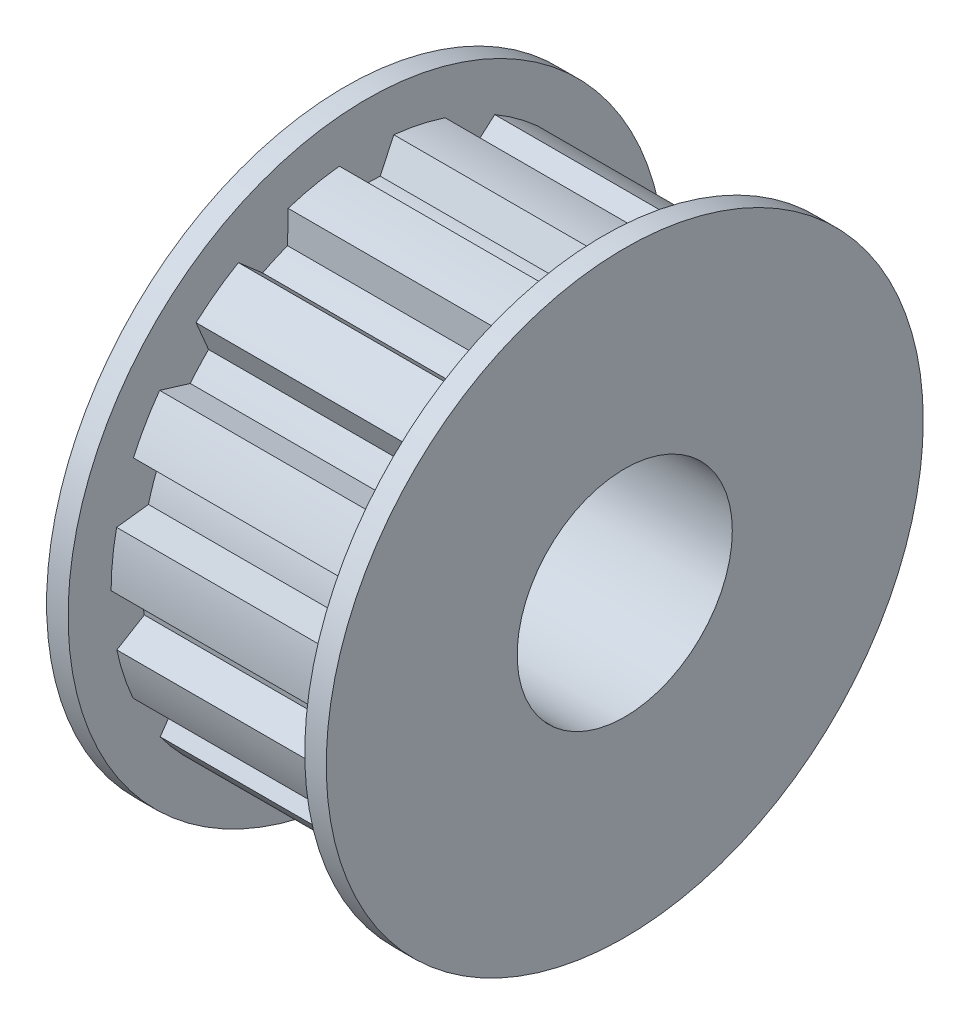
SolidWorks part; units mm, degrees
ref_plane "Front Plane" through (0, 0, 0) normal (0, 0, 1) x (1, 0, 0)
ref_plane "Top Plane" through (0, 0, 0) normal (0, 1, 0) x (1, 0, 0)
ref_plane "Right Plane" through (0, 0, 0) normal (1, 0, 0) x (0, 0, -1)
sketch "Sketch1" plane through (0, 0, 0) normal (1, 0, 0) x (0, 0, -1)
  line L0 (0, 11.875) -> (0, 0) construction
  circle A0 centre (0, 0) radius 11.875
  circle A1 centre (0, 0) radius 5
  point P19 (0, 0)
  dimension "D1" = 23.75
  dimension "D2" = 10
extrude "Boss-Extrude1" add sketch "Sketch1" along normal blind 11
sketch "Sketch2" plane through (0, 0, 0) normal (-1, 0, 0) x (0, 0, 1)
  line L0 (0, 0) -> (0, 11.875) construction
  line L1 (1.2649, 11.8074) -> (0.6346, 10.4558)
  line L2 (-1.2649, 11.8074) -> (-0.6346, 10.4558)
  line L3 (5.9581, 10.2721) -> (4.8325, 9.2937)
  line L4 (3.647, 11.3011) -> (3.673, 9.8099)
  line L5 (9.621, 6.9607) -> (8.1948, 6.5247)
  line L6 (7.9282, 8.8407) -> (7.3455, 7.4679)
  line L7 (11.6204, 2.4457) -> (10.1401, 2.6275)
  line L8 (10.8387, 4.8517) -> (9.7479, 3.8346)
  line L9 (11.6105, -2.4922) -> (10.3321, -1.7241)
  line L10 (11.875, 0.0238) -> (10.4648, -0.4618)
  line L11 (9.5931, -6.9992) -> (8.7376, -5.7775)
  line L12 (10.858, -4.8083) -> (9.3723, -4.6783)
  line L13 (5.9169, -10.2959) -> (5.6323, -8.8319)
  line L14 (7.9636, -8.8089) -> (6.6592, -8.0859)
  line L15 (1.2176, -11.8124) -> (1.5531, -10.3592)
  line L16 (3.6922, -11.2864) -> (2.7946, -10.0953)
  line L17 (-3.6922, -11.2864) -> (-2.7946, -10.0953)
  line L18 (-1.2176, -11.8124) -> (-1.5531, -10.3592)
  line L19 (-7.9636, -8.8089) -> (-6.6592, -8.0859)
  line L20 (-5.9169, -10.2959) -> (-5.6323, -8.8319)
  line L21 (-10.858, -4.8083) -> (-9.3723, -4.6783)
  line L22 (-9.5931, -6.9992) -> (-8.7376, -5.7775)
  line L23 (-11.875, 0.0238) -> (-10.4648, -0.4618)
  line L24 (-11.6105, -2.4922) -> (-10.3321, -1.7241)
  line L25 (-10.8387, 4.8517) -> (-9.7479, 3.8346)
  line L26 (-11.6204, 2.4457) -> (-10.1401, 2.6275)
  line L27 (-7.9282, 8.8407) -> (-7.3455, 7.4679)
  line L28 (-9.621, 6.9607) -> (-8.1948, 6.5247)
  line L29 (-3.647, 11.3011) -> (-3.673, 9.8099)
  line L30 (-5.9581, 10.2721) -> (-4.8325, 9.2937)
  circle A0 centre (0, 0) radius 11.875 construction
  arc A1 (1.2649, 11.8074) -> (-1.2649, 11.8074) centre (0, 0) ccw
  arc A2 (0.6346, 10.4558) -> (-0.6346, 10.4558) centre (0, 0) ccw
  arc A3 (5.9581, 10.2721) -> (3.647, 11.3011) centre (0, 0) ccw
  arc A4 (4.8325, 9.2937) -> (3.673, 9.8099) centre (0, 0) ccw
  arc A5 (9.621, 6.9607) -> (7.9282, 8.8407) centre (0, 0) ccw
  arc A6 (8.1948, 6.5247) -> (7.3455, 7.4679) centre (0, 0) ccw
  arc A7 (11.6204, 2.4457) -> (10.8387, 4.8517) centre (0, 0) ccw
  arc A8 (10.1401, 2.6275) -> (9.7479, 3.8346) centre (0, 0) ccw
  arc A9 (11.6105, -2.4922) -> (11.875, 0.0238) centre (0, 0) ccw
  arc A10 (10.3321, -1.7241) -> (10.4648, -0.4618) centre (0, 0) ccw
  arc A11 (9.5931, -6.9992) -> (10.858, -4.8083) centre (0, 0) ccw
  arc A12 (8.7376, -5.7775) -> (9.3723, -4.6783) centre (0, 0) ccw
  arc A13 (5.9169, -10.2959) -> (7.9636, -8.8089) centre (0, 0) ccw
  arc A14 (5.6323, -8.8319) -> (6.6592, -8.0859) centre (0, 0) ccw
  arc A15 (1.2176, -11.8124) -> (3.6922, -11.2864) centre (0, 0) ccw
  arc A16 (1.5531, -10.3592) -> (2.7946, -10.0953) centre (0, 0) ccw
  arc A17 (-3.6922, -11.2864) -> (-1.2176, -11.8124) centre (0, 0) ccw
  arc A18 (-2.7946, -10.0953) -> (-1.5531, -10.3592) centre (0, 0) ccw
  arc A19 (-7.9636, -8.8089) -> (-5.9169, -10.2959) centre (0, 0) ccw
  arc A20 (-6.6592, -8.0859) -> (-5.6323, -8.8319) centre (0, 0) ccw
  arc A21 (-10.858, -4.8083) -> (-9.5931, -6.9992) centre (0, 0) ccw
  arc A22 (-9.3723, -4.6783) -> (-8.7376, -5.7775) centre (0, 0) ccw
  arc A23 (-11.875, 0.0238) -> (-11.6105, -2.4922) centre (0, 0) ccw
  arc A24 (-10.4648, -0.4618) -> (-10.3321, -1.7241) centre (0, 0) ccw
  arc A25 (-10.8387, 4.8517) -> (-11.6204, 2.4457) centre (0, 0) ccw
  arc A26 (-9.7479, 3.8346) -> (-10.1401, 2.6275) centre (0, 0) ccw
  arc A27 (-7.9282, 8.8407) -> (-9.621, 6.9607) centre (0, 0) ccw
  arc A28 (-7.3455, 7.4679) -> (-8.1948, 6.5247) centre (0, 0) ccw
  arc A29 (-3.647, 11.3011) -> (-5.9581, 10.2721) centre (0, 0) ccw
  arc A30 (-3.673, 9.8099) -> (-4.8325, 9.2937) centre (0, 0) ccw
  point P10 (0, 10.475)
  point P18 (4.2606, 9.5694)
  point P23 (7.7844, 7.0091)
  point P28 (9.9623, 3.237)
  point P33 (10.4176, -1.0949)
  point P38 (9.0716, -5.2375)
  point P43 (6.1571, -8.4745)
  point P48 (2.1779, -10.2461)
  point P53 (-2.1779, -10.2461)
  point P58 (-6.1571, -8.4745)
  point P63 (-9.0716, -5.2375)
  point P68 (-10.4176, -1.0949)
  point P73 (-9.9623, 3.237)
  point P78 (-7.7844, 7.0091)
  point P83 (-4.2606, 9.5694)
  point P159 (0, 0)
  dimension "D1" = 1.4
  dimension "D2" = 25
  dimension "D3" = 0.635
  dimension "D4" = 15
extrude "Cut-Extrude1" cut sketch "Sketch2" against normal through all
sketch "Sketch4" plane through (11, 0, 0) normal (1, 0, 0) x (0, 0, -1)
  circle A0 centre (0, 0) radius 13.875
  circle A1 centre (0, 0) radius 5 construction
  circle A2 centre (0, 0) radius 5
  circle A3 centre (0, 0) radius 11.875 construction
  dimension "D1" = 2
extrude "Boss-Extrude2" add sketch "Sketch4" along normal blind 1
pattern_linear "LPattern1" count 2 spacing 12 along (-1, 0, 0) of "Boss-Extrude2"
